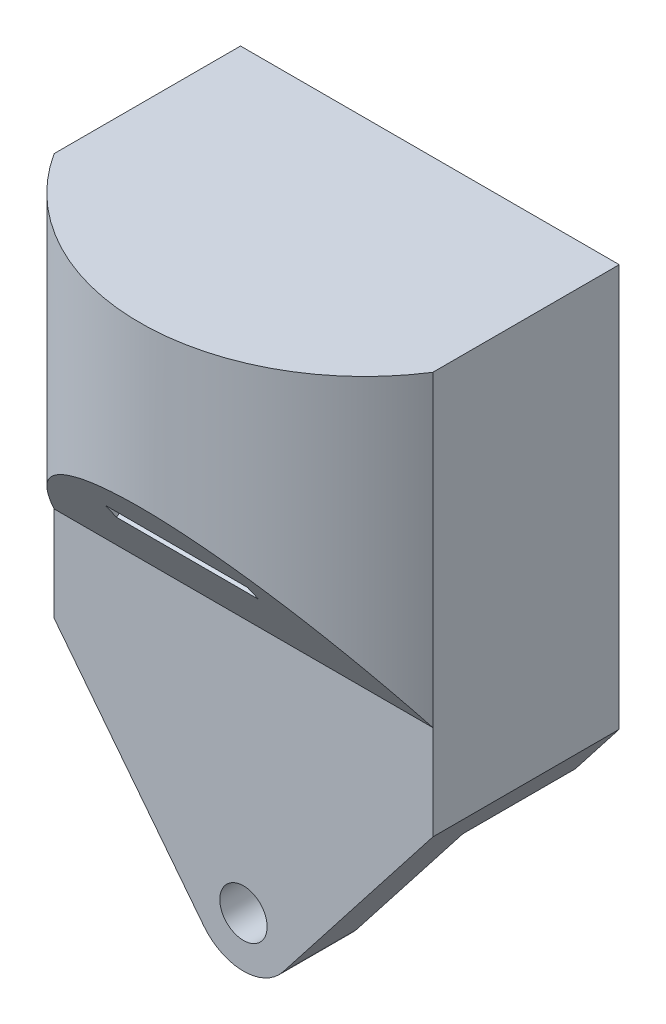
SolidWorks part; units mm, degrees
other "Детальный элемент1"
material "3.3320 (EN-AW 5019)"
ref_plane "Спереди" through (0, 0, 0) normal (0, 0, 1) x (1, 0, 0)
ref_plane "Сверху" through (0, 0, 0) normal (0, 1, 0) x (1, 0, 0)
ref_plane "Справа" through (0, 0, 0) normal (1, 0, 0) x (0, 0, -1)
sketch "Эскиз1" plane through (0, 0, 0) normal (0, 0, 1) x (1, 0, 0)
  line L0 (0, 0) -> (0, 136)
  line L1 (0, 136) -> (128, 136)
  line L2 (128, 136) -> (128, 0)
  line L3 (128, 0) -> (77.3962, -64.7699)
  line L4 (0, 0) -> (50.6038, -64.7699)
  arc A0 (50.6038, -64.7699) -> (77.3962, -64.7699) centre (64, -54.3037) ccw
  dimension "D5" = 17
  dimension "D1" = 136
  dimension "D2" = 128
  dimension "D3" = 38
  dimension "D4" = 38
extrude "Бобышка-Вытянуть1" add sketch "Эскиз1" along normal blind 25
sketch "Эскиз2" plane through (0, 136, 0) normal (0, 1, 0) x (1, 0, 0)
  line L0 (0, -25) -> (128, -25)
  line L1 (64, -60) -> (162.502, -60) construction
  arc A0 (0, -25) -> (128, -25) centre (64, 16.0143) ccw
  dimension "D1" = 76.0143
  dimension "D2" = 35
extrude "Бобышка-Вытянуть2" add sketch "Эскиз2" against normal blind 104 contours A0 L0
sketch "Эскиз3" plane through (128, 0, 0) normal (1, 0, 0) x (0, 0, -1)
  line L0 (-25, 32) -> (-60, 32)
  line L1 (-60, 32) -> (-60, 82)
  line L2 (-60, 82) -> (-25, 32)
  line L3 (-25, 32) -> (-25, 136) construction
  line L4 (-25, 136) -> (-60, 136) construction
  line L5 (-60, 136) -> (-60, 32) construction
  dimension "D1" = 54
extrude "Вырез-Вытянуть1" cut sketch "Эскиз3" against normal through all
sketch "Эскиз4" plane through (0, -1.2215, 1.745) normal (0, -0.5735, 0.8192) x (1, 0, 0)
  line L0 (0, 40.552) -> (128, 40.552) construction
  line L1 (40, 80.052) -> (88, 80.052)
  line L2 (40, 80.052) -> (40, 73.552)
  line L3 (40, 73.552) -> (88, 73.552)
  line L4 (88, 80.052) -> (88, 73.552)
  point P7 (64, 80.052)
  point P9 (64, 40.552)
  dimension "D1" = 48
  dimension "D2" = 33
  dimension "D3" = 6.5
extrude "Вырез-Вытянуть2" cut sketch "Эскиз4" against normal blind 3
sketch "Эскиз5" plane through (0, 0, 25) normal (0, 0, 1) x (1, 0, 0)
  circle A0 centre (64, -54.3037) radius 8
  arc A1 (50.6038, -64.7699) -> (77.3962, -64.7699) centre (64, -54.3037) ccw construction
extrude "Вырез-Вытянуть3" cut sketch "Эскиз5" against normal through all
sketch "Эскиз6" plane through (0, 0, 0) normal (0, 0, -1) x (-1, 0, 0)
  line L0 (-128, 136) -> (0, 136)
  line L1 (0, 136) -> (0, 0)
  line L2 (0, 0) -> (-14.8444, -19)
  line L3 (0, 0) -> (-50.6038, -64.7699) construction
  line L4 (-14.8444, -19) -> (-113.1556, -19)
  line L5 (-77.3962, -64.7699) -> (-128, 0) construction
  line L6 (-113.1556, -19) -> (-128, 0)
  line L7 (-128, 0) -> (-128, 136)
  dimension "D1" = 155
  dimension "D2" = 128
extrude "Бобышка-Вытянуть3" add sketch "Эскиз6" along normal blind 38
ref_plane "Средняя плоскость" through (64, 0, 0) normal (1, 0, 0) x (0, 0, -1)
